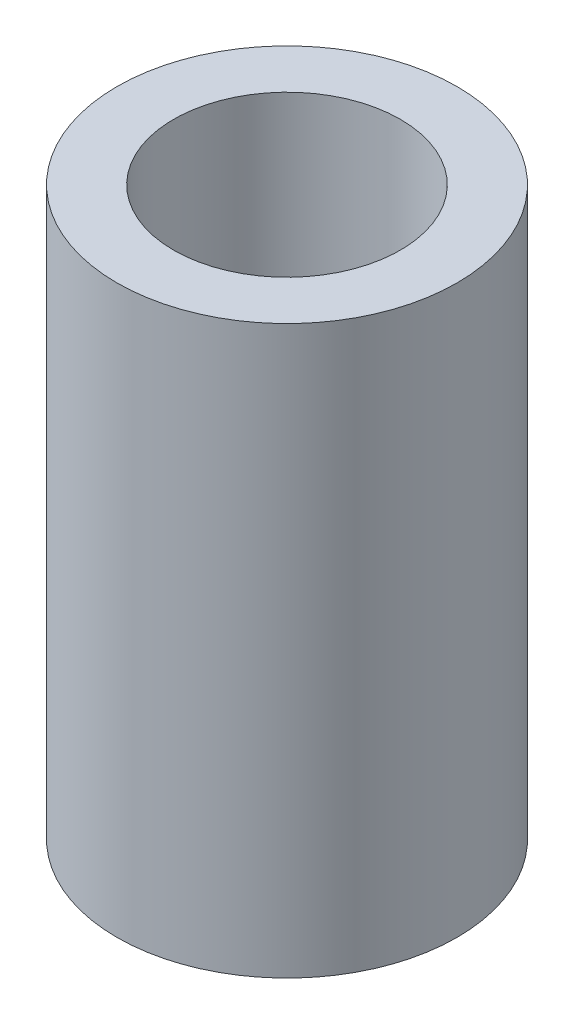
SolidWorks part; units mm, degrees
ref_plane "Front Plane" through (0, 0, 0) normal (0, 0, 1) x (1, 0, 0)
ref_plane "Top Plane" through (0, 0, 0) normal (0, 1, 0) x (1, 0, 0)
ref_plane "Right Plane" through (0, 0, 0) normal (1, 0, 0) x (0, 0, -1)
other "Configuration Table"
sketch "Sketch1" plane through (0, 0, 0) normal (0, 1, 0) x (1, 0, 0)
  circle A0 centre (0, 0) radius 1.5
  circle A1 centre (0, 0) radius 1
  dimension "D1" = 2
  dimension "D2" = 3
extrude "Boss-Extrude1" add sketch "Sketch1" along normal blind 5
